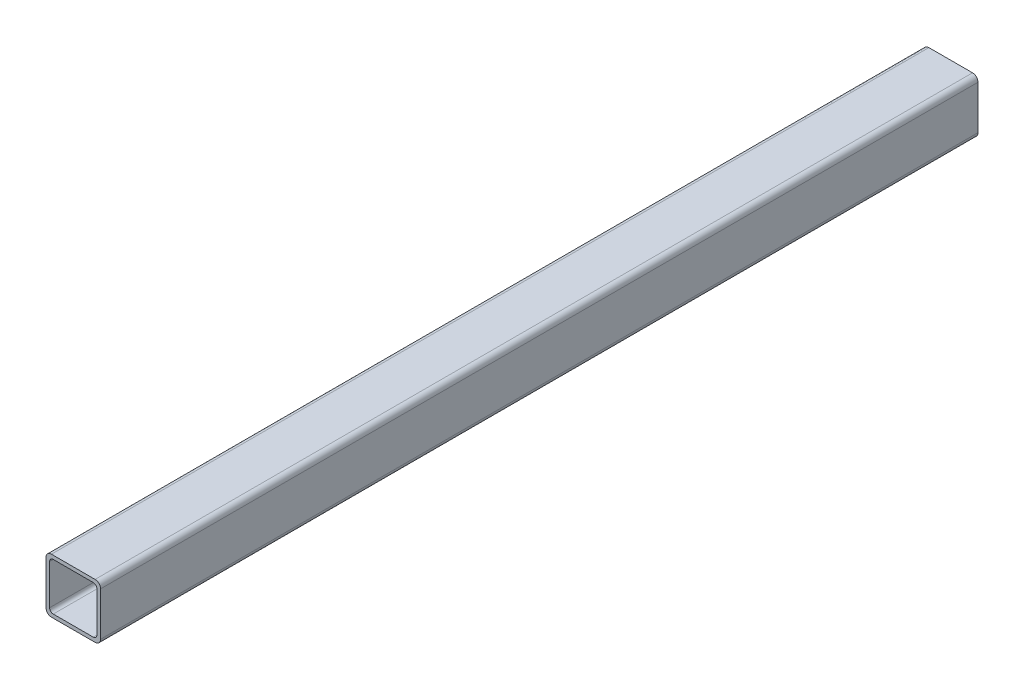
SolidWorks part; units mm, degrees
material "AISI 1020"
ref_plane "Спереди" through (0, 0, 0) normal (0, 0, 1) x (1, 0, 0)
ref_plane "Сверху" through (0, 0, 0) normal (0, 1, 0) x (1, 0, 0)
ref_plane "Справа" through (0, 0, 0) normal (1, 0, 0) x (0, 0, -1)
sketch "Эскиз1" plane through (0, 0, 0) normal (0, 0, 1) x (1, 0, 0)
  line L2 (0, 0) -> (0, -1970) construction
  line B0 (-27, 0) -> (-3, 0)
  line B1 (-30, -3) -> (-30, -27)
  line B2 (-27, -30) -> (-3, -30)
  line B3 (0, -3) -> (0, -27)
  line B4 (-26, -2) -> (-4, -2)
  line B5 (-28, -4) -> (-28, -26)
  line B6 (-26, -28) -> (-4, -28)
  line B7 (-2, -4) -> (-2, -26)
  arc B8 (-30, -27) -> (-27, -30) centre (-27, -27) ccw
  arc B9 (-3, -30) -> (0, -27) centre (-3, -27) ccw
  arc B10 (-3, 0) -> (0, -3) centre (-3, -3) cw
  arc B11 (-27, 0) -> (-30, -3) centre (-27, -3) ccw
  arc B12 (-28, -26) -> (-26, -28) centre (-26, -26) ccw
  arc B13 (-4, -28) -> (-2, -26) centre (-4, -26) ccw
  arc B14 (-4, -2) -> (-2, -4) centre (-4, -4) cw
  arc B15 (-26, -2) -> (-28, -4) centre (-26, -4) ccw
sketch_block_instance "Блок-30х30х2-1"
sketch_block "Блок-30х30х2" parameters "D3"=3, "D4"=2, "D1"=30, "D2"=2
extrude "Бобышка-Вытянуть1" add sketch "Эскиз1" against normal up to vertex (482.5 mm away)
